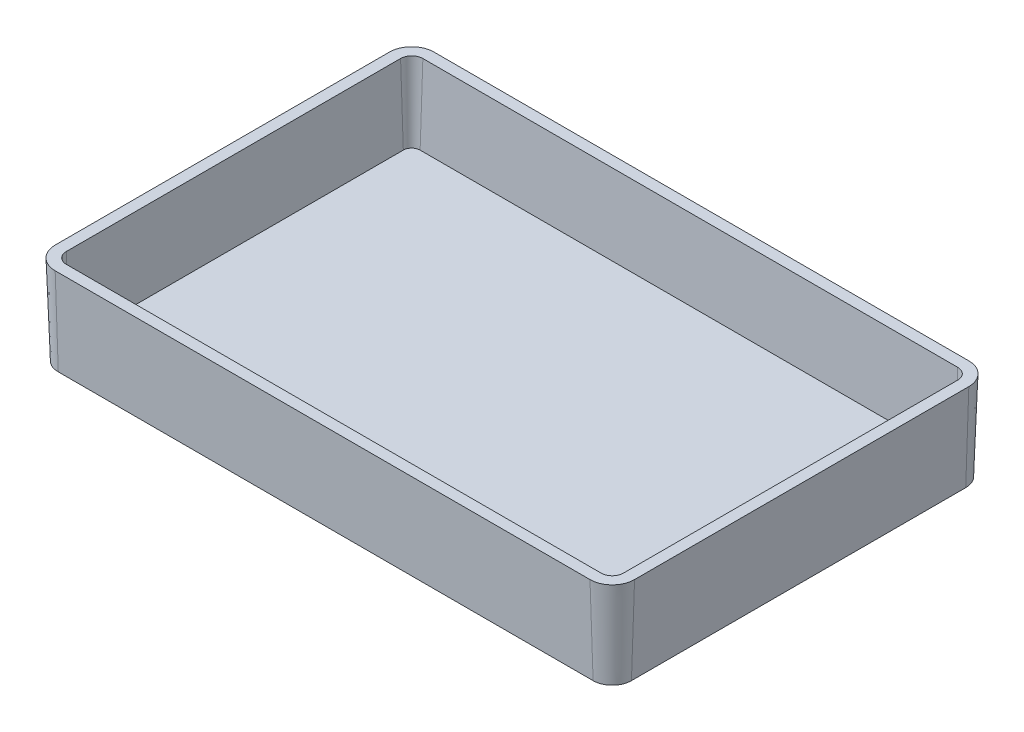
SolidWorks part; units mm, degrees
ref_plane "Front Plane" through (0, 0, 0) normal (0, 0, 1) x (1, 0, 0)
ref_plane "Top Plane" through (0, 0, 0) normal (0, 1, 0) x (1, 0, 0)
ref_plane "Right Plane" through (0, 0, 0) normal (1, 0, 0) x (0, 0, -1)
sketch "Sketch1" plane through (0, 0, 0) normal (0, 1, 0) x (1, 0, 0)
  line L1 (-12, -8.5) -> (12, -8.5)
  line L2 (-13, -7.5) -> (-13, 7.5)
  line L3 (-12, 8.5) -> (12, 8.5)
  line L4 (13, -7.5) -> (13, 7.5)
  line L5 (-13, -8.5) -> (13, 8.5) construction
  line L6 (-13, 8.5) -> (13, -8.5) construction
  arc A0 (-13, 7.5) -> (-12, 8.5) centre (-12, 7.5) cw
  arc A1 (13, 7.5) -> (12, 8.5) centre (12, 7.5) ccw
  arc A2 (13, -7.5) -> (12, -8.5) centre (12, -7.5) cw
  arc A3 (-12, -8.5) -> (-13, -7.5) centre (-12, -7.5) cw
  point P0 (0, 0)
  dimension "D3" = 1
  dimension "D1" = 26
  dimension "D2" = 17
extrude "Boss-Extrude1" add sketch "Sketch1" against normal blind 4 draft 2
shell "Shell1" thickness 0.5
